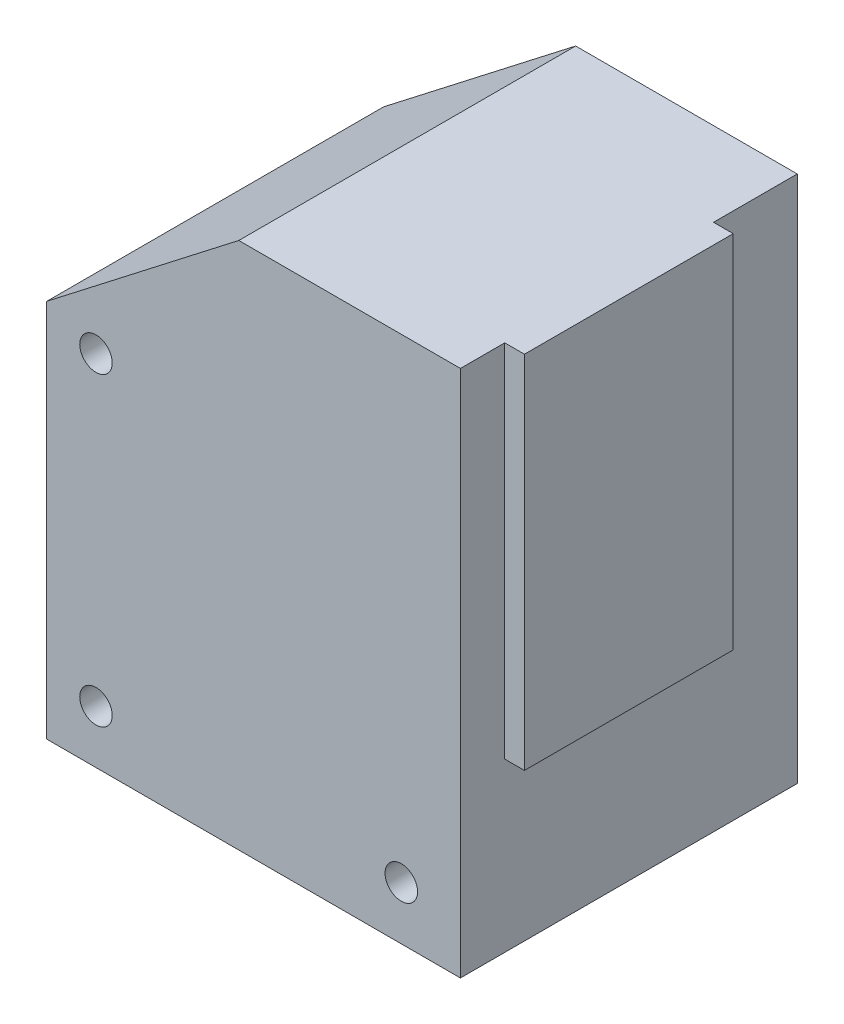
SolidWorks part; units mm, degrees
ref_plane "Front Plane" through (0, 0, 0) normal (0, 0, 1) x (1, 0, 0)
ref_plane "Top Plane" through (0, 0, 0) normal (0, 1, 0) x (1, 0, 0)
ref_plane "Right Plane" through (0, 0, 0) normal (1, 0, 0) x (0, 0, -1)
sketch "Sketch1" plane through (0, 0, 0) normal (0, 0, 1) x (1, 0, 0)
  line L0 (0, 38.5) -> (19.5, 53.6)
  line L1 (0, 0) -> (42, 0)
  line L2 (0, 0) -> (0, 38.5)
  line L3 (19.5, 53.6) -> (42, 53.6)
  line L4 (42, 0) -> (42, 53.6)
  dimension "D1" = 53.6
  dimension "D2" = 42
  dimension "D3" = 22.5
  dimension "D4" = 38.5
extrude "Boss-Extrude1" add sketch "Sketch1" along normal blind 34.2
sketch "Sketch2" plane through (0, 0, 0) normal (0, -1, 0) x (1, 0, 0)
  line L0 (42, 34.2) -> (42, 0) construction
  line L1 (0, 34.2) -> (42, 34.2) construction
  circle A0 centre (26, 23.7) radius 8
  dimension "D3" = 16
  dimension "D1" = 16
  dimension "D2" = 10.5
extrude "Cut-Extrude1" cut sketch "Sketch2" against normal blind 10
sketch "Sketch3" plane through (42, 0, 0) normal (1, 0, 0) x (0, 0, -1)
  line L0 (-34.2, 53.6) -> (0, 53.6) construction
  line L1 (-29.7, 53.6) -> (-8.5, 53.6)
  line L2 (-29.7, 53.6) -> (-29.7, 17)
  line L3 (-29.7, 17) -> (-8.5, 17)
  line L4 (-8.5, 53.6) -> (-8.5, 17)
  line L5 (-34.2, 0) -> (-34.2, 53.6) construction
  line L6 (0, 0) -> (0, 53.6) construction
  line L7 (-34.2, 0) -> (0, 0) construction
  dimension "D1" = 4.5
  dimension "D2" = 8.5
  dimension "D3" = 17
extrude "Boss-Extrude2" add sketch "Sketch3" along normal blind 2
sketch "Sketch4" plane through (0, 0, 0) normal (0, 0, -1) x (-1, 0, 0)
  line L0 (-42, 2) -> (-40, 0)
  line L1 (-42, 0) -> (-42, 53.6) construction
  line L2 (0, 0) -> (-42, 0) construction
  line L3 (-40, 0) -> (-42, 0)
  line L4 (-42, 0) -> (-42, 2)
  line L5 (0, 2) -> (-2, 0)
  line L6 (0, 38.5) -> (0, 0) construction
  line L7 (-2, 0) -> (0, 0)
  line L8 (0, 0) -> (0, 2)
  dimension "D1" = 45
  dimension "D2" = 2
  dimension "D3" = 2
extrude "Cut-Extrude3" [suppressed] cut sketch "Sketch4" against normal through all
fillet "Fillet1" [suppressed] radius 1
sketch "Sketch5" plane through (0, 0, 0) normal (0, 0, -1) x (-1, 0, 0)
  line L1 (-36, 5.4) -> (-5, 5.4) construction
  line L2 (-36, 5.4) -> (-36, 36.4) construction
  line L3 (-36, 36.4) -> (-5, 36.4) construction
  line L4 (-5, 5.4) -> (-5, 36.4) construction
  line L5 (0, 0) -> (-42, 0) construction
  line L6 (0, 38.5) -> (0, 0) construction
  circle A0 centre (-36, 5.4) radius 1.65
  circle A1 centre (-5, 5.4) radius 1.65
  circle A2 centre (-5, 36.4) radius 1.65
  dimension "D3" = 3.3
  dimension "D1" = 31
  dimension "D2" = 31
  dimension "D4" = 5
  dimension "D5" = 5.4
extrude "Cut-Extrude4" cut sketch "Sketch5" against normal through all
